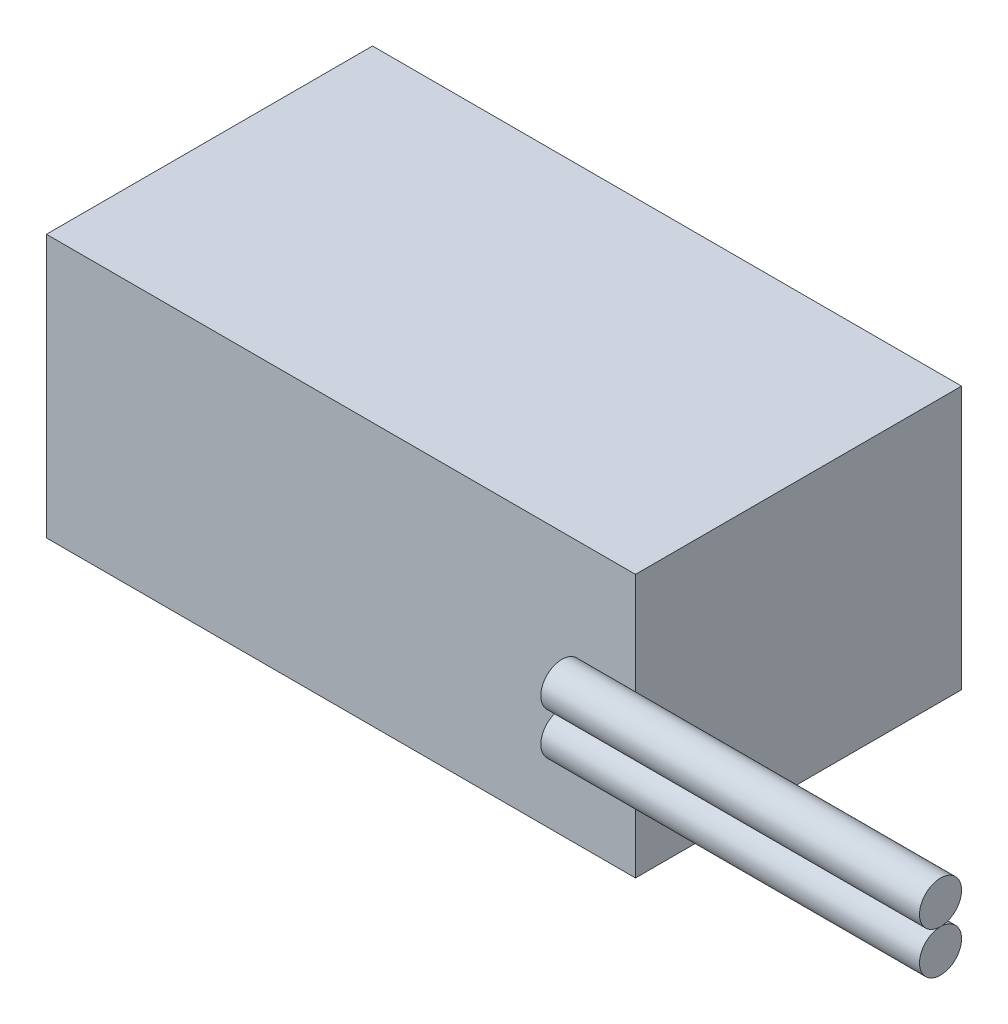
SolidWorks part; units mm, degrees
ref_plane "Front Plane" through (0, 0, 0) normal (0, 0, 1) x (1, 0, 0)
ref_plane "Top Plane" through (0, 0, 0) normal (0, 1, 0) x (1, 0, 0)
ref_plane "Right Plane" through (0, 0, 0) normal (1, 0, 0) x (0, 0, -1)
sketch "Sketch1" plane through (0, 0, 0) normal (0, 0, 1) x (1, 0, 0)
  line L1 (28, -12.5) -> (-28, -12.5)
  line L2 (28, -12.5) -> (28, 12.5)
  line L3 (28, 12.5) -> (-28, 12.5)
  line L4 (-28, -12.5) -> (-28, 12.5)
  line L5 (28, -12.5) -> (-28, 12.5) construction
  line L6 (28, 12.5) -> (-28, -12.5) construction
  point P0 (0, 0)
  dimension "D1" = 56
  dimension "D2" = 25
extrude "Boss-Extrude1" add sketch "Sketch1" along normal mid plane 31
sketch "Sketch2" plane through (28, 0, 0) normal (1, 0, 0) x (0, 0, -1)
  line L0 (-15.5, -12.5) -> (-15.5, 12.5) construction
  line L1 (-17.5, -2) -> (-17.5, 2) construction
  circle A0 centre (-17.5, 2) radius 2
  circle A1 centre (-17.5, -2) radius 2
  point P6 (-17.5, 0)
  dimension "D1" = 4
  dimension "D2" = 4
extrude "Boss-Extrude2" add sketch "Sketch2" against normal blind 5 and the other way blind 31 separate body
